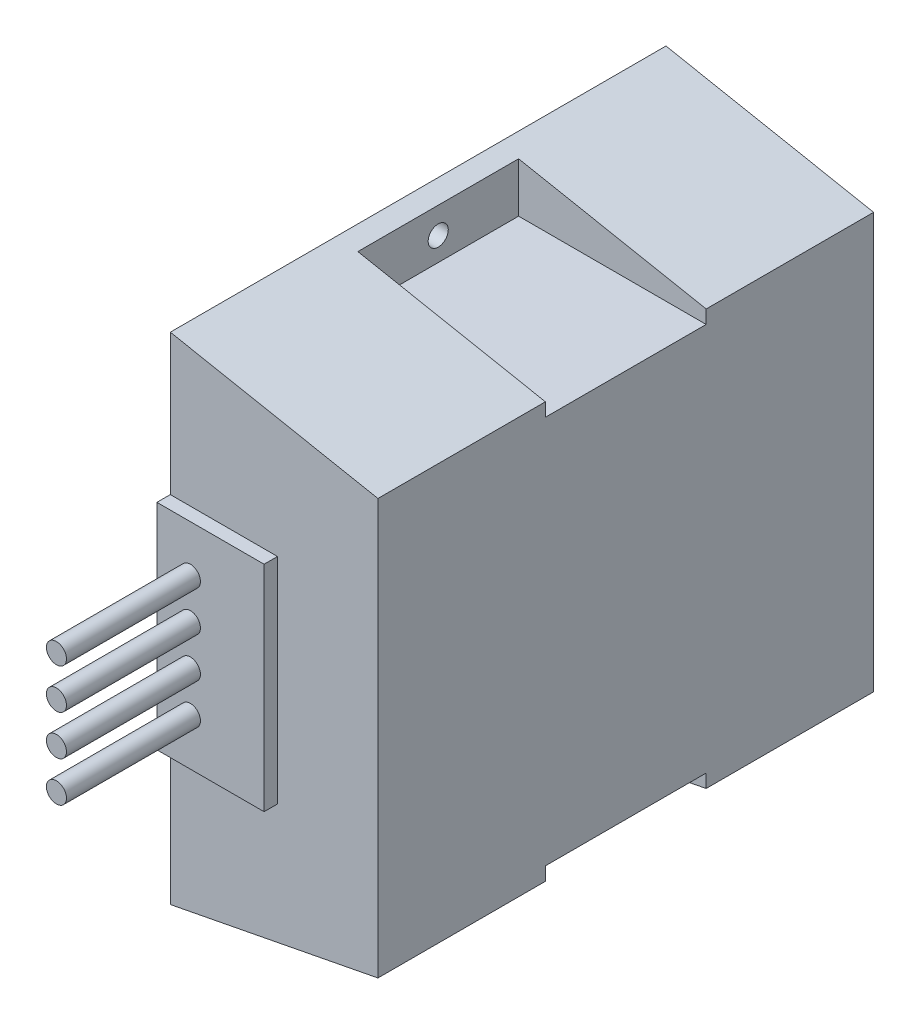
SolidWorks part; units mm, degrees
ref_plane "前视基准面" through (0, 0, 0) normal (0, 0, 1) x (1, 0, 0)
ref_plane "上视基准面" through (0, 0, 0) normal (0, 1, 0) x (1, 0, 0)
ref_plane "右视基准面" through (0, 0, 0) normal (1, 0, 0) x (0, 0, -1)
sketch "草图1" plane through (0, 0, 0) normal (1, 0, 0) x (0, 0, -1)
  line L1 (-37, 37) -> (37, 37)
  line L2 (-37, 37) -> (-37, -37)
  line L3 (-37, -37) -> (37, -37)
  line L4 (37, 37) -> (37, -37)
  line L5 (-37, 37) -> (37, -37) construction
  line L6 (-37, -37) -> (37, 37) construction
  point P0 (0, 0)
  dimension "D1" = 74
  dimension "D2" = 74
ref_plane "基准面1" through (31, 0, 0) normal (1, 0, 0) x (0, 0, -1)
sketch "草图2" plane through (31, 0, 0) normal (1, 0, 0) x (0, 0, -1)
  line L0 (37, 37) -> (37, -37) construction
  line L1 (-37, 31) -> (37, 31)
  line L2 (-37, 31) -> (-37, -31)
  line L3 (-37, -31) -> (37, -31)
  line L4 (37, 31) -> (37, -31)
  line L5 (-37, 31) -> (37, -31) construction
  line L6 (-37, -31) -> (37, 31) construction
  point P0 (0, 0)
  dimension "D1" = 62
loft "放样1" add profiles "草图2", "草图1"
sketch "草图3" plane through (31, 0, 0) normal (1, 0, 0) x (0, 0, -1)
  line L0 (37, 37) -> (-37, 37) construction
  line L1 (-12, 37) -> (12, 37)
  line L2 (-12, 37) -> (-12, 29)
  line L3 (-12, 29) -> (12, 29)
  line L4 (12, 37) -> (12, 29)
  line L5 (-12, 37) -> (12, 29) construction
  line L6 (-12, 29) -> (12, 37) construction
  point P0 (0, 33)
  dimension "D1" = 8
  dimension "D2" = 0
  dimension "D3" = 24
  dimension "D4" = 0
extrude "切除-拉伸1" cut sketch "草图3" against normal blind 28
mirror "镜向1" about plane through (0, 0, 0) normal (0, 1, 0) of "切除-拉伸1"
sketch "草图4" plane through (0, 0, 37) normal (0, 0, 1) x (1, 0, 0)
  line L0 (0, 37) -> (0, -37) construction
  line L1 (16, 16) -> (0, 16)
  line L2 (16, 16) -> (16, -16)
  line L3 (16, -16) -> (0, -16)
  line L4 (0, 16) -> (0, -16)
  line L5 (16, 16) -> (0, -16) construction
  line L6 (16, -16) -> (0, 16) construction
  point P0 (8, 0)
  dimension "D1" = 0
  dimension "D2" = 0
  dimension "D3" = 32
  dimension "D4" = 16
extrude "凸台-拉伸1" add sketch "草图4" along normal blind 2
sketch "草图5" plane through (0, 0, 39) normal (0, 0, 1) x (1, 0, 0)
  line L0 (0, 16) -> (0, -16) construction
  circle A0 centre (5, -3) radius 1.5
  circle A1 centre (5, -9) radius 1.5
  dimension "D1" = 3
  dimension "D2" = 3
  dimension "D5" = 5
  dimension "D6" = 5
  dimension "D3" = 3
  dimension "D4" = 6
extrude "凸台-拉伸2" add sketch "草图5" along normal blind 20
mirror "镜向2" about plane through (0, 0, 0) normal (0, 1, 0) of "凸台-拉伸2"
sketch "草图6" plane through (0, 0, 0) normal (-1, 0, 0) x (0, 0, 1)
  circle A0 centre (0, -32.5) radius 1.5
  dimension "D1" = 3
  dimension "D2" = 0
  dimension "D3" = 32.5
extrude "切除-拉伸2" cut sketch "草图6" against normal through all
mirror "镜向3" about plane through (0, 0, 0) normal (0, 1, 0) of "切除-拉伸2"
